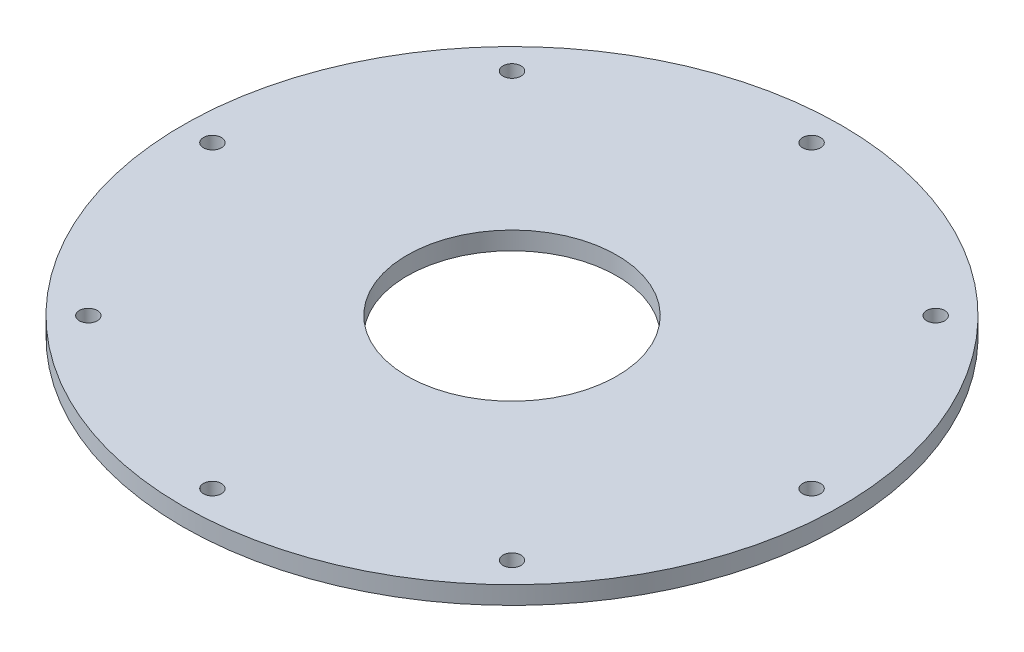
SolidWorks part; units mm, degrees
ref_plane "Front Plane" through (0, 0, 0) normal (0, 0, 1) x (1, 0, 0)
ref_plane "Top Plane" through (0, 0, 0) normal (0, 1, 0) x (1, 0, 0)
ref_plane "Right Plane" through (0, 0, 0) normal (1, 0, 0) x (0, 0, -1)
sketch "Sketch1" plane through (0, 0, 0) normal (0, 1, 0) x (1, 0, 0)
  circle A0 centre (0, 0) radius 55
  dimension "D1" = 110
extrude "Boss-Extrude1" add sketch "Sketch1" along normal blind 3
sketch "Sketch2" plane through (0, 3, 0) normal (0, 1, 0) x (1, 0, 0)
  circle A0 centre (0, 0) radius 17.5
extrude "Cut-Extrude1" cut sketch "Sketch2" against normal blind 3
sketch "Sketch4" plane through (0, 3, 0) normal (0, 1, 0) x (1, 0, 0)
  circle A0 centre (0, 50) radius 1.5
  dimension "D2" = 3
  dimension "D1" = 50
extrude "Cut-Extrude2" cut sketch "Sketch4" against normal blind 3
pattern_circular "CirPattern1" count 8 over 360 about axis through (0, 0, 0) along (0, 1, 0) of "Cut-Extrude2"
